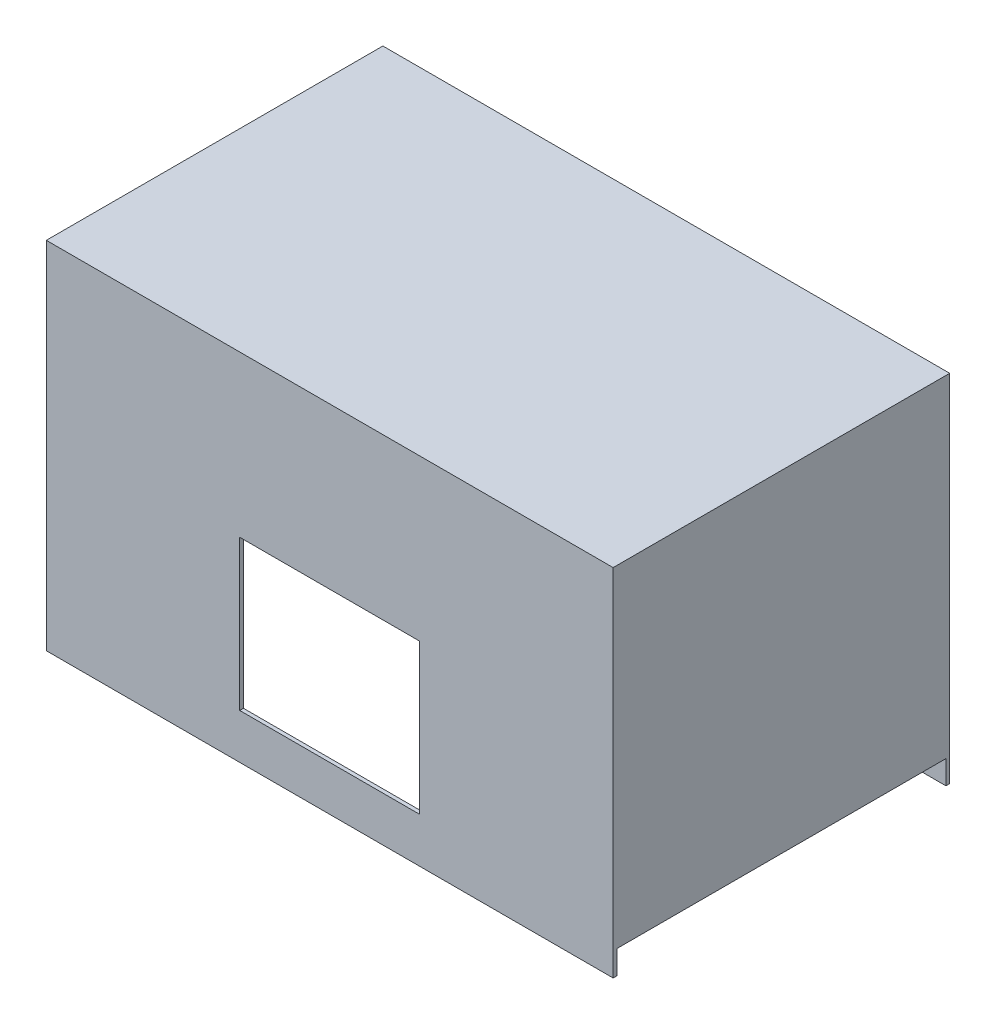
SolidWorks part; units mm, degrees
ref_plane "Plan de face" through (0, 0, 0) normal (0, 0, 1) x (1, 0, 0)
ref_plane "Plan de dessus" through (0, 0, 0) normal (0, 1, 0) x (1, 0, 0)
ref_plane "Plan de droite" through (0, 0, 0) normal (1, 0, 0) x (0, 0, -1)
sketch "Esquisse1" plane through (0, 0, 0) normal (0, 0, 1) x (1, 0, 0)
  line L1 (-480, 300.99) -> (480, 300.99)
  line L2 (-480, 300.99) -> (-480, -300.99)
  line L3 (-480, -300.99) -> (480, -300.99)
  line L4 (480, 300.99) -> (480, -300.99)
  point P4 (-480, 0)
  point P13 (0, 300.99)
  dimension "D1" = 601.98
  dimension "D2" = 960
  dimension "D3" = 480
extrude "Boss.-Extru.1" add sketch "Esquisse1" along normal mid plane 570
sketch "Esquisse4" plane through (0, -300.99, 0) normal (0, -1, 0) x (1, 0, 0)
  line L0 (-480, -285) -> (480, -285) construction
  line L1 (-473.65, 278.65) -> (473.65, 278.65)
  line L2 (-473.65, 278.65) -> (-473.65, -278.65)
  line L3 (-473.65, -278.65) -> (473.65, -278.65)
  line L4 (473.65, 278.65) -> (473.65, -278.65)
  line L5 (480, 285) -> (480, -285) construction
  line L6 (-480, 285) -> (480, 285) construction
  line L8 (-480, 285) -> (-480, -285) construction
  dimension "D1" = 6.35
  dimension "D2" = 6.35
  dimension "D3" = 6.35
  dimension "D4" = 6.35
sketch "Esquisse5" plane through (480, 0, 0) normal (1, 0, 0) x (0, 0, -1)
  line L0 (-285, -300.99) -> (285, -300.99) construction
  line L1 (-278.65, -300.99) -> (278.65, -300.99)
  line L2 (-278.65, -300.99) -> (-278.65, -260.99)
  line L3 (-278.65, -260.99) -> (278.65, -260.99)
  line L4 (278.65, -300.99) -> (278.65, -260.99)
  line L5 (285, -300.99) -> (285, 300.99) construction
  line L6 (-285, -300.99) -> (-285, 300.99) construction
  dimension "D1" = 40
  dimension "D2" = 6.35
  dimension "D3" = 6.35
sketch "Esquisse6" plane through (0, 0, 285) normal (0, 0, 1) x (1, 0, 0)
  line L1 (-152.4, 29.21) -> (152.4, 29.21)
  line L2 (-152.4, 29.21) -> (-152.4, -224.79)
  line L3 (-152.4, -224.79) -> (152.4, -224.79)
  line L4 (152.4, 29.21) -> (152.4, -224.79)
  line L5 (-480, -300.99) -> (480, -300.99) construction
  point P6 (0, 29.21)
  point P8 (0, -224.79)
  dimension "D1" = 76.2
  dimension "D2" = 304.8
  dimension "D3" = 254
extrude "Enlèv. mat.-Extru.7" cut sketch "Esquisse4" against normal blind 595.63
extrude "Enlèv. mat.-Extru.8" cut sketch "Esquisse5" against normal through all
extrude "Enlèv. mat.-Extru.9" cut sketch "Esquisse6" against normal blind 25.4
